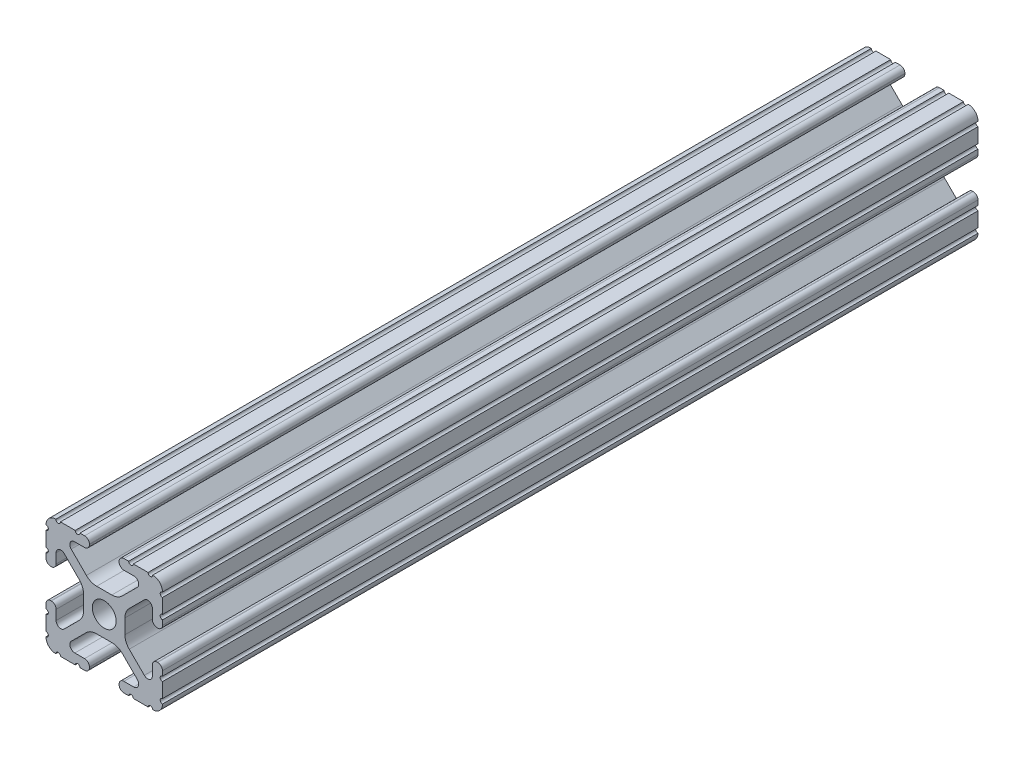
SolidWorks part; units mm, degrees
material "6061 Alloy"
ref_plane "Front Plane" through (0, 0, 0) normal (0, 0, 1) x (1, 0, 0)
ref_plane "Top Plane" through (0, 0, 0) normal (0, 1, 0) x (1, 0, 0)
ref_plane "Right Plane" through (0, 0, 0) normal (1, 0, 0) x (0, 0, -1)
sketch "Sketch1" plane through (0, 0, 0) normal (0, 0, 1) x (1, 0, 0)
  line L88 (-7.1797, -8.6452) -> (-3.9523, -5.4237)
  line L89 (-1.7093, -4.4958) -> (1.7093, -4.4958)
  line L90 (3.9523, -5.4237) -> (7.1797, -8.6452)
  line L91 (6.4164, -10.4902) -> (4.2875, -10.4902)
  line L92 (3.2385, -11.5392) -> (3.2385, -11.651)
  line L93 (4.2875, -12.7) -> (5.3171, -12.7)
  line L94 (6.3331, -12.7) -> (9.5504, -12.7)
  line L95 (12.7, -9.5504) -> (12.7, -6.3331)
  line L96 (12.7, -5.3171) -> (12.7, -4.2875)
  line L97 (11.651, -3.2385) -> (11.5392, -3.2385)
  line L98 (10.4902, -4.2875) -> (10.4902, -6.4021)
  line L99 (8.7371, -7.1294) -> (5.441, -3.8408)
  line L100 (4.5085, -1.5932) -> (4.5085, 1.5932)
  line L101 (5.441, 3.8408) -> (8.7371, 7.1294)
  line L102 (10.4902, 6.4021) -> (10.4902, 4.2875)
  line L103 (11.5392, 3.2385) -> (11.651, 3.2385)
  line L104 (12.7, 4.2875) -> (12.7, 5.3171)
  line L105 (12.7, 6.3331) -> (12.7, 9.5504)
  line L106 (9.5504, 12.7) -> (6.3331, 12.7)
  line L107 (5.3171, 12.7) -> (4.2875, 12.7)
  line L108 (3.2385, 11.651) -> (3.2385, 11.5392)
  line L109 (4.2875, 10.4902) -> (6.4768, 10.4902)
  line L110 (7.207, 8.7244) -> (3.8983, 5.4232)
  line L111 (1.6558, 4.4958) -> (-1.6558, 4.4958)
  line L112 (-3.8983, 5.4232) -> (-7.207, 8.7244)
  line L113 (-6.4768, 10.4902) -> (-4.2875, 10.4902)
  line L114 (-3.2385, 11.5392) -> (-3.2385, 11.651)
  line L115 (-4.2875, 12.7) -> (-5.3171, 12.7)
  line L116 (-6.3331, 12.7) -> (-9.5504, 12.7)
  line L117 (-12.7, 9.5504) -> (-12.7, 6.3331)
  line L118 (-12.7, 5.3171) -> (-12.7, 4.2875)
  line L119 (-11.651, 3.2385) -> (-11.5392, 3.2385)
  line L120 (-10.4902, 4.2875) -> (-10.4902, 6.4021)
  line L121 (-8.7371, 7.1294) -> (-5.441, 3.8408)
  line L122 (-4.5085, 1.5932) -> (-4.5085, -1.5932)
  line L123 (-5.441, -3.8408) -> (-8.7371, -7.1294)
  line L124 (-10.4902, -6.4021) -> (-10.4902, -4.2875)
  line L125 (-11.5392, -3.2385) -> (-11.651, -3.2385)
  line L126 (-12.7, -4.2875) -> (-12.7, -5.3171)
  line L127 (-12.7, -6.3331) -> (-12.7, -9.5504)
  line L128 (-9.5504, -12.7) -> (-6.3331, -12.7)
  line L129 (-5.3171, -12.7) -> (-4.2875, -12.7)
  line L130 (-3.2385, -11.651) -> (-3.2385, -11.5392)
  line L131 (-4.2875, -10.4902) -> (-6.4164, -10.4902)
  circle A1 centre (0, 0) radius 2.6035
  arc A104 (-7.1797, -8.6452) -> (-6.4164, -10.4902) centre (-6.4164, -9.4098) ccw
  arc A105 (-1.7093, -4.4958) -> (-3.9523, -5.4237) centre (-1.7093, -7.6708) ccw
  arc A106 (3.9523, -5.4237) -> (1.7093, -4.4958) centre (1.7093, -7.6708) ccw
  arc A107 (6.4164, -10.4902) -> (7.1797, -8.6452) centre (6.4164, -9.4098) ccw
  arc A108 (4.2875, -10.4902) -> (3.2385, -11.5392) centre (4.2875, -11.5392) ccw
  arc A109 (3.2385, -11.651) -> (4.2875, -12.7) centre (4.2875, -11.651) ccw
  arc A110 (6.3331, -12.7) -> (5.3171, -12.7) centre (5.8251, -12.7) ccw
  arc A111 (10.5664, -12.6998) -> (9.5504, -12.7) centre (10.0584, -12.7) ccw
  arc A112 (10.5664, -12.6998) -> (12.6998, -10.5664) centre (10.5918, -10.5918) ccw
  arc A113 (12.7, -9.5504) -> (12.6998, -10.5664) centre (12.7, -10.0584) ccw
  arc A114 (12.7, -5.3171) -> (12.7, -6.3331) centre (12.7, -5.8251) ccw
  arc A115 (12.7, -4.2875) -> (11.651, -3.2385) centre (11.651, -4.2875) ccw
  arc A116 (11.5392, -3.2385) -> (10.4902, -4.2875) centre (11.5392, -4.2875) ccw
  arc A117 (8.7371, -7.1294) -> (10.4902, -6.4021) centre (9.4628, -6.4021) ccw
  arc A118 (4.5085, -1.5932) -> (5.441, -3.8408) centre (7.6835, -1.5932) ccw
  arc A119 (5.441, 3.8408) -> (4.5085, 1.5932) centre (7.6835, 1.5932) ccw
  arc A120 (10.4902, 6.4021) -> (8.7371, 7.1294) centre (9.4628, 6.4021) ccw
  arc A121 (10.4902, 4.2875) -> (11.5392, 3.2385) centre (11.5392, 4.2875) ccw
  arc A122 (11.651, 3.2385) -> (12.7, 4.2875) centre (11.651, 4.2875) ccw
  arc A123 (12.7, 6.3331) -> (12.7, 5.3171) centre (12.7, 5.8251) ccw
  arc A124 (12.6998, 10.5664) -> (12.7, 9.5504) centre (12.7, 10.0584) ccw
  arc A125 (12.6998, 10.5664) -> (10.5664, 12.6998) centre (10.5918, 10.5918) ccw
  arc A126 (9.5504, 12.7) -> (10.5664, 12.6998) centre (10.0584, 12.7) ccw
  arc A127 (5.3171, 12.7) -> (6.3331, 12.7) centre (5.8251, 12.7) ccw
  arc A128 (4.2875, 12.7) -> (3.2385, 11.651) centre (4.2875, 11.651) ccw
  arc A129 (3.2385, 11.5392) -> (4.2875, 10.4902) centre (4.2875, 11.5392) ccw
  arc A130 (7.207, 8.7244) -> (6.4768, 10.4902) centre (6.4768, 9.4563) ccw
  arc A131 (1.6558, 4.4958) -> (3.8983, 5.4232) centre (1.6558, 7.6708) ccw
  arc A132 (-3.8983, 5.4232) -> (-1.6558, 4.4958) centre (-1.6558, 7.6708) ccw
  arc A133 (-6.4768, 10.4902) -> (-7.207, 8.7244) centre (-6.4768, 9.4563) ccw
  arc A134 (-4.2875, 10.4902) -> (-3.2385, 11.5392) centre (-4.2875, 11.5392) ccw
  arc A135 (-3.2385, 11.651) -> (-4.2875, 12.7) centre (-4.2875, 11.651) ccw
  arc A136 (-6.3331, 12.7) -> (-5.3171, 12.7) centre (-5.8251, 12.7) ccw
  arc A137 (-10.5664, 12.6998) -> (-9.5504, 12.7) centre (-10.0584, 12.7) ccw
  arc A138 (-10.5664, 12.6998) -> (-12.6998, 10.5664) centre (-10.5918, 10.5918) ccw
  arc A139 (-12.7, 9.5504) -> (-12.6998, 10.5664) centre (-12.7, 10.0584) ccw
  arc A140 (-12.7, 5.3171) -> (-12.7, 6.3331) centre (-12.7, 5.8251) ccw
  arc A141 (-12.7, 4.2875) -> (-11.651, 3.2385) centre (-11.651, 4.2875) ccw
  arc A142 (-11.5392, 3.2385) -> (-10.4902, 4.2875) centre (-11.5392, 4.2875) ccw
  arc A143 (-8.7371, 7.1294) -> (-10.4902, 6.4021) centre (-9.4628, 6.4021) ccw
  arc A144 (-4.5085, 1.5932) -> (-5.441, 3.8408) centre (-7.6835, 1.5932) ccw
  arc A145 (-5.441, -3.8408) -> (-4.5085, -1.5932) centre (-7.6835, -1.5932) ccw
  arc A146 (-10.4902, -6.4021) -> (-8.7371, -7.1294) centre (-9.4628, -6.4021) ccw
  arc A147 (-10.4902, -4.2875) -> (-11.5392, -3.2385) centre (-11.5392, -4.2875) ccw
  arc A148 (-11.651, -3.2385) -> (-12.7, -4.2875) centre (-11.651, -4.2875) ccw
  arc A149 (-12.7, -6.3331) -> (-12.7, -5.3171) centre (-12.7, -5.8251) ccw
  arc A150 (-12.6998, -10.5664) -> (-12.7, -9.5504) centre (-12.7, -10.0584) ccw
  arc A151 (-12.6998, -10.5664) -> (-10.5664, -12.6998) centre (-10.5918, -10.5918) ccw
  arc A152 (-9.5504, -12.7) -> (-10.5664, -12.6998) centre (-10.0584, -12.7) ccw
  arc A153 (-5.3171, -12.7) -> (-6.3331, -12.7) centre (-5.8251, -12.7) ccw
  arc A154 (-4.2875, -12.7) -> (-3.2385, -11.651) centre (-4.2875, -11.651) ccw
  arc A155 (-3.2385, -11.5392) -> (-4.2875, -10.4902) centre (-4.2875, -11.5392) ccw
extrude "Boss-Extrude1" add sketch "Sketch1" along normal mid plane 177.8
